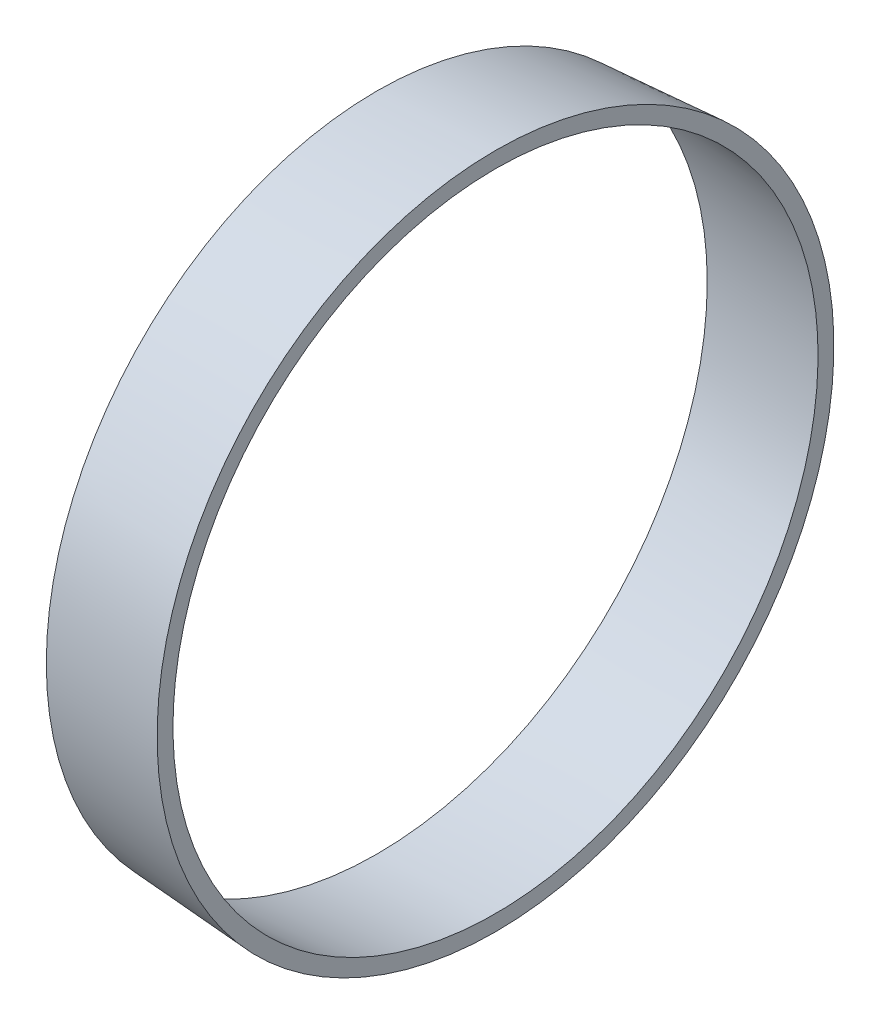
SolidWorks part; units mm, degrees
ref_plane "Front Plane" through (0, 0, 0) normal (0, 0, 1) x (1, 0, 0)
ref_plane "Top Plane" through (0, 0, 0) normal (0, 1, 0) x (1, 0, 0)
ref_plane "Right Plane" through (0, 0, 0) normal (1, 0, 0) x (0, 0, -1)
sketch "Sketch1" plane through (0, 0, 0) normal (0, 0, 1) x (1, 0, 0)
  line L0 (0, 0) -> (2000, 0) construction
  line L1 (100, 1670) -> (700, 1710)
  line L2 (700, 1710) -> (700, 1630)
  line L3 (700, 1630) -> (100, 1670)
revolve "Revolve1" add sketch "Sketch1" angle 360 about L0
sketch "Sketch2" plane through (0, 0, 0) normal (0, 0, 1) x (1, 0, 0)
  line L0 (0, 0) -> (3000, 0) construction
  line L1 (700, 1630) -> (700, 1710)
  line L2 (700, -1710) -> (700, 1710) construction
  line L3 (700, 1710) -> (750, 1750)
  line L4 (750, 1750) -> (700, 1710)
  line L5 (700, 1710) -> (2150, 1710)
  line L6 (2150, 1710) -> (2150, 1750)
  line L7 (2150, 1750) -> (2200, 1750)
  line L8 (2200, 1750) -> (2200, 1630)
  line L9 (2200, 1630) -> (700, 1630)
